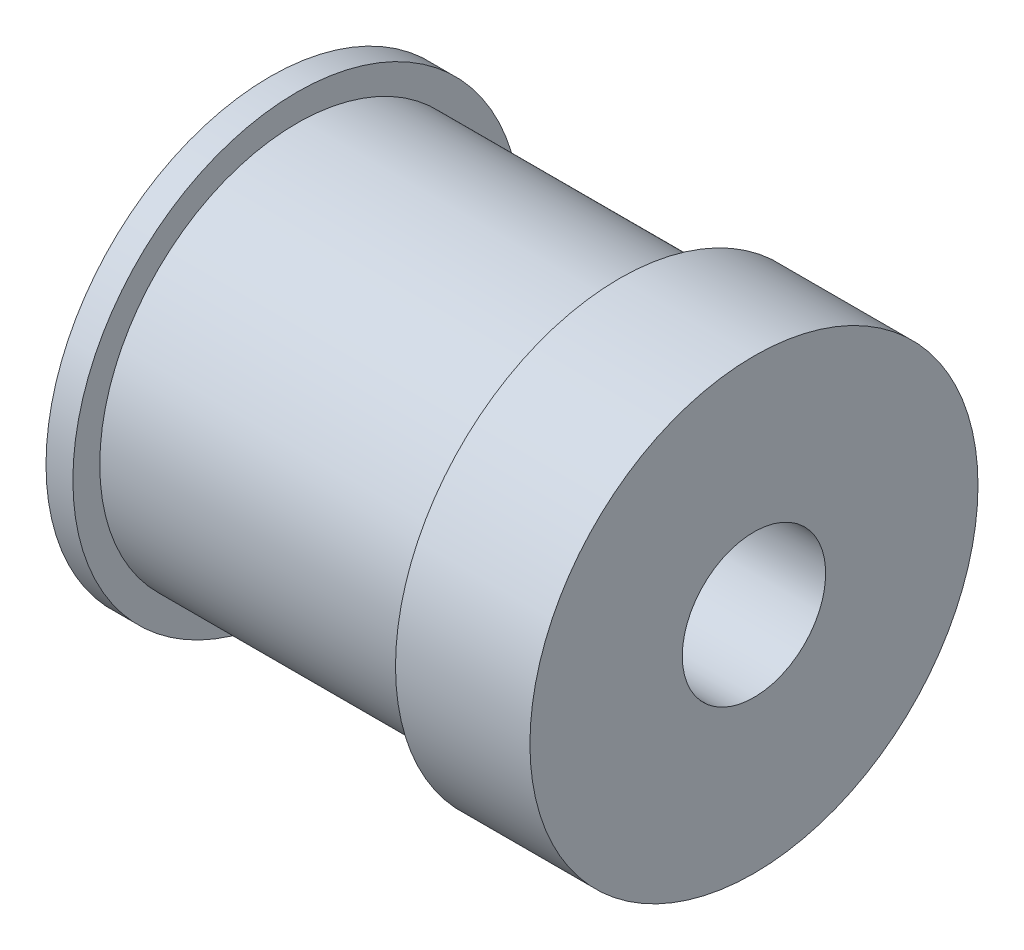
SolidWorks part; units mm, degrees
ref_plane "Front Plane" through (0, 0, 0) normal (0, 0, 1) x (1, 0, 0)
ref_plane "Top Plane" through (0, 0, 0) normal (0, 1, 0) x (1, 0, 0)
ref_plane "Right Plane" through (0, 0, 0) normal (1, 0, 0) x (0, 0, -1)
sketch "Sketch1" plane through (0, 0, 0) normal (0, 0, 1) x (1, 0, 0)
  line L0 (-58.1666, 0) -> (60.2282, 0) construction
  line L4 (59.2282, 12.5) -> (51.7282, 12.5)
  line L5 (51.7282, 12.5) -> (51.7282, 11)
  line L6 (51.7282, 11) -> (33.7282, 11)
  line L7 (33.7282, 11) -> (33.7282, 12.5)
  line L8 (33.7282, 12.5) -> (32.2282, 12.5)
  line L13 (32.2282, 4.0817) -> (32.2282, 4)
  line L14 (32.2282, 4) -> (59.2282, 4)
  line L16 (32.2282, 4.0817) -> (32.2282, 12.5)
  line L17 (59.2282, 12.5) -> (59.2282, 4)
  dimension "D1" = 7.5
  dimension "D2" = 11
  dimension "D3" = 4
  dimension "D4" = 18
  dimension "D5" = 1.5
  dimension "D6" = 12.5
revolve "Revolve1" add sketch "Sketch1" angle 360 about L0
